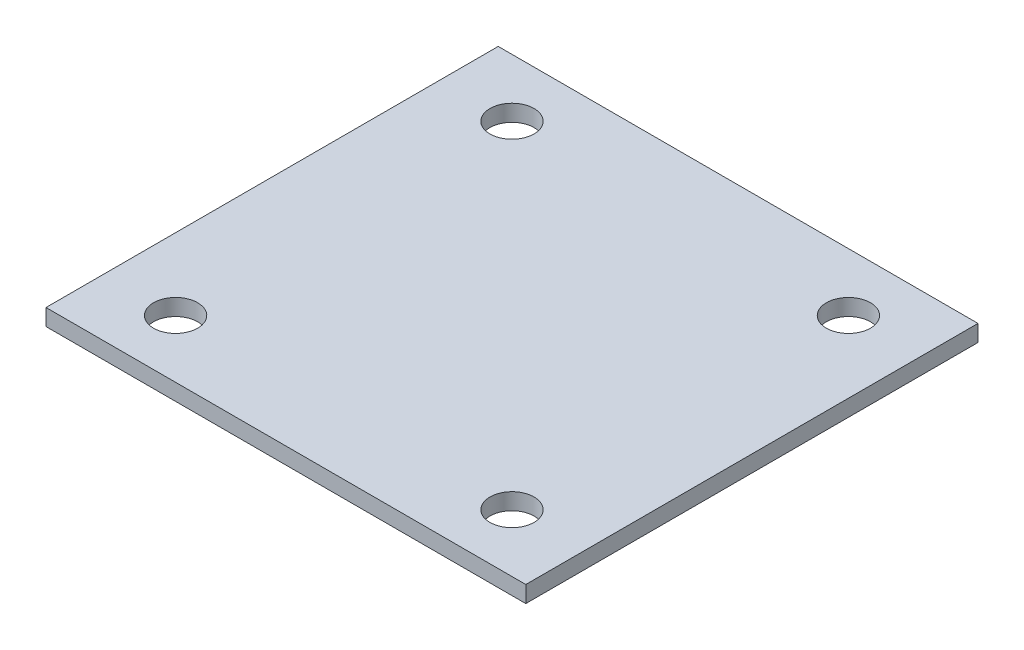
SolidWorks part; units mm, degrees
ref_plane "前视基准面" through (0, 0, 0) normal (0, 0, 1) x (1, 0, 0)
ref_plane "上视基准面" through (0, 0, 0) normal (0, 1, 0) x (1, 0, 0)
ref_plane "右视基准面" through (0, 0, 0) normal (1, 0, 0) x (0, 0, -1)
other "Configuration Table"
sketch "草图1" plane through (0, 0, 0) normal (0, 1, 0) x (1, 0, 0)
  line L0 (-21.75, 0) -> (21.75, 0) construction
  line L1 (-21.75, -20.5) -> (21.75, -20.5)
  line L2 (-21.75, -20.5) -> (-21.75, 20.5)
  line L3 (-21.75, 20.5) -> (21.75, 20.5)
  line L4 (21.75, -20.5) -> (21.75, 20.5)
  line L5 (-21.75, -20.5) -> (21.75, 20.5) construction
  line L6 (-21.75, 20.5) -> (21.75, -20.5) construction
  line L7 (0, -20.5) -> (0, 20.5) construction
  circle A0 centre (-15.25, 15.25) radius 2
  circle A4 centre (15.25, 15.25) radius 2
  circle A5 centre (15.25, -15.25) radius 2
  circle A6 centre (-15.25, -15.25) radius 2
  point P0 (0, 0)
  point P17 (0, 0)
  point P20 (0, 0)
  dimension "D3" = 4
  dimension "D4" = 30.5
  dimension "D5" = 30.5
  dimension "D1" = 41
  dimension "D2" = 43.5
extrude "凸台-拉伸1" add sketch "草图1" along normal blind 1.5
